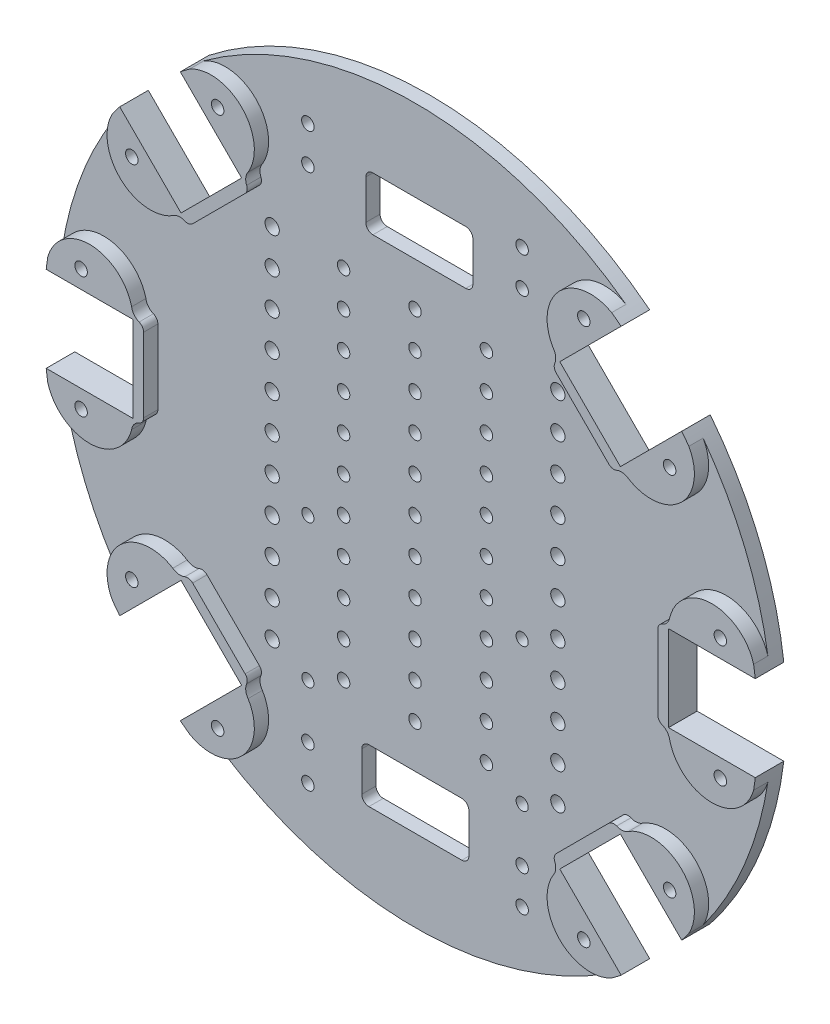
SolidWorks part; units mm, degrees
material "ABS PC"
ref_plane "Front Plane" through (0, 0, 0) normal (0, 0, 1) x (1, 0, 0)
ref_plane "Top Plane" through (0, 0, 0) normal (0, 1, 0) x (1, 0, 0)
ref_plane "Right Plane" through (0, 0, 0) normal (1, 0, 0) x (0, 0, -1)
sketch "Sketch1" plane through (0, 0, 0) normal (0, 0, 1) x (1, 0, 0)
  line L0 (0, 0) -> (0, 100) construction
  line L5 (44.5477, 61.5183) -> (61.7144, 78.685)
  line L6 (44.5477, 61.5183) -> (61.5183, 44.5477)
  line L7 (-12, 75) -> (12, 75) construction
  line L8 (-12, 75) -> (-12, 99.2774) construction
  line L9 (12, 75) -> (12, 99.2774) construction
  line L10 (-17, 89.5) -> (17, 89.5) construction
  line L11 (61.5183, 44.5477) -> (78.685, 61.7144)
  line L12 (75, 12) -> (99.2774, 12)
  line L13 (75, 12) -> (75, -12)
  line L14 (75, -12) -> (99.2774, -12)
  line L15 (61.5183, -44.5477) -> (78.685, -61.7144)
  line L16 (61.5183, -44.5477) -> (44.5477, -61.5183)
  line L17 (44.5477, -61.5183) -> (61.7144, -78.685)
  line L18 (12, -75) -> (12, -99.2774) construction
  line L19 (12, -75) -> (-12, -75) construction
  line L20 (-12, -75) -> (-12, -99.2774) construction
  line L21 (-44.5477, -61.5183) -> (-61.7144, -78.685)
  line L22 (-44.5477, -61.5183) -> (-61.5183, -44.5477)
  line L23 (-61.5183, -44.5477) -> (-78.685, -61.7144)
  line L24 (-75, -12) -> (-99.2774, -12)
  line L25 (-75, -12) -> (-75, 12)
  line L26 (-75, 12) -> (-99.2774, 12)
  line L27 (-61.5183, 44.5477) -> (-78.685, 61.7144)
  line L28 (-61.5183, 44.5477) -> (-44.5477, 61.5183)
  line L29 (-44.5477, 61.5183) -> (-61.7144, 78.685)
  circle A1 centre (0, 0) radius 100
  circle A2 centre (-17, 89.5) radius 1.75 construction
  circle A3 centre (17, 89.5) radius 1.75 construction
  circle A4 centre (51.2652, 75.3069) radius 1.75
  circle A5 centre (75.3069, 51.2652) radius 1.75
  circle A6 centre (89.5, 17) radius 1.75
  circle A7 centre (89.5, -17) radius 1.75
  circle A8 centre (75.3069, -51.2652) radius 1.75
  circle A9 centre (51.2652, -75.3069) radius 1.75
  circle A10 centre (17, -89.5) radius 1.75 construction
  circle A11 centre (-17, -89.5) radius 1.75 construction
  circle A12 centre (-51.2652, -75.3069) radius 1.75
  circle A13 centre (-75.3069, -51.2652) radius 1.75
  circle A14 centre (-89.5, -17) radius 1.75
  circle A15 centre (-89.5, 17) radius 1.75
  circle A16 centre (-75.3069, 51.2652) radius 1.75
  circle A17 centre (-51.2652, 75.3069) radius 1.75
  point P2 (0, 89.5)
  point P4 (0, 75)
  point P12 (0, 75)
  point P19 (0, 89.5)
  dimension "150" = 200
  dimension "D7" = 3.5
  dimension "D2" = 25
  dimension "D3" = 8
  dimension "D4" = 24
  dimension "D5" = 14.5
  dimension "D6" = 34
extrude "Boss-Extrude1" add sketch "Sketch1" along normal blind 4 contours L12 A1 L11 L6 L5 L29 L28 L27 L26 L25 L24 L23 L22 L21 L17 L16 L15 L14 L13 A15 A14 A9 A8 A5 A4 A6 A7 A12 A13 A16 A17
sketch "Sketch2" plane through (0, 0, 4) normal (0, 0, 1) x (1, 0, 0)
  line L0 (0, 35) -> (0, -35) construction
  line L1 (-35, 35) -> (35, 35) construction
  line L2 (-35, 35) -> (-35, -35) construction
  line L3 (-35, -35) -> (35, -35) construction
  line L4 (35, 35) -> (35, -35) construction
  line L5 (-35, 35) -> (35, -35) construction
  line L6 (-35, -35) -> (35, 35) construction
  line L7 (0, 35) -> (0, 80)
  line L8 (-30, -15) -> (30, -15) construction
  line L9 (-30, -15) -> (-30, -55) construction
  line L10 (-30, -55) -> (30, -55) construction
  line L11 (30, -15) -> (30, -55) construction
  line L12 (-30, -15) -> (30, -55) construction
  line L13 (-30, -55) -> (30, -15) construction
  line L14 (-30, 80) -> (30, 80)
  line L15 (0, -55) -> (0, -80)
  line L16 (30, -80) -> (-30, -80)
  line L17 (0, 0) -> (-40, 0) construction
  line L18 (0, 0) -> (40, 0) construction
  line L19 (0, 10) -> (-40, 10)
  line L20 (0, 10) -> (40, 10)
  line L21 (0, 20) -> (-40, 20)
  line L22 (0, 20) -> (40, 20)
  line L23 (0, 30) -> (-40, 30)
  line L24 (0, 30) -> (40, 30)
  line L25 (0, 40) -> (-40, 40)
  line L26 (0, 40) -> (40, 40)
  line L27 (0, 50) -> (-40, 50)
  line L28 (0, 50) -> (40, 50)
  line L29 (0, -10) -> (40, -10)
  line L30 (0, -10) -> (-40, -10)
  line L31 (0, -20) -> (40, -20)
  line L32 (0, -20) -> (-40, -20)
  line L33 (0, -30) -> (40, -30)
  line L34 (0, -30) -> (-40, -30)
  line L35 (0, -40) -> (40, -40)
  line L36 (0, -40) -> (-40, -40)
  line L37 (0, -50) -> (40, -50)
  line L38 (0, -50) -> (-40, -50)
  line L39 (30, -70) -> (-30, -70)
  line L40 (-30, 70) -> (30, 70)
  circle A0 centre (0, 0) radius 100
  circle A1 centre (-30, -55) radius 1.7
  circle A2 centre (-30, -15) radius 1.7
  circle A3 centre (30, -55) radius 1.7
  circle A4 centre (30, -15) radius 1.7
  circle A5 centre (-30, 80) radius 1.75
  circle A6 centre (30, 80) radius 1.75
  circle A7 centre (-30, -80) radius 1.75
  circle A8 centre (30, -80) radius 1.75
  circle A9 centre (-40, 0) radius 2
  circle A10 centre (-20, 0) radius 1.75
  circle A11 centre (0, 0) radius 1.75
  circle A12 centre (40, 0) radius 2
  circle A13 centre (20, 0) radius 1.75
  circle A14 centre (20, 10) radius 1.75
  circle A15 centre (40, 10) radius 2
  circle A16 centre (-20, 10) radius 1.75
  circle A17 centre (-40, 10) radius 2
  circle A18 centre (0, 10) radius 1.75
  circle A19 centre (20, 20) radius 1.75
  circle A20 centre (40, 20) radius 2
  circle A21 centre (-20, 20) radius 1.75
  circle A22 centre (-40, 20) radius 2
  circle A23 centre (0, 20) radius 1.75
  circle A24 centre (20, 30) radius 1.75
  circle A25 centre (40, 30) radius 2
  circle A26 centre (-20, 30) radius 1.75
  circle A27 centre (-40, 30) radius 2
  circle A28 centre (0, 30) radius 1.75
  circle A29 centre (20, 40) radius 1.75
  circle A30 centre (40, 40) radius 2
  circle A31 centre (-20, 40) radius 1.75
  circle A32 centre (-40, 40) radius 2
  circle A33 centre (0, 40) radius 1.75
  circle A34 centre (20, 50) radius 1.75
  circle A35 centre (40, 50) radius 2
  circle A36 centre (-20, 50) radius 1.75
  circle A37 centre (-40, 50) radius 2
  circle A38 centre (0, 50) radius 1.75
  circle A39 centre (40, -10) radius 2
  circle A40 centre (0, -10) radius 1.75
  circle A41 centre (20, -10) radius 1.75
  circle A42 centre (-20, -10) radius 1.75
  circle A43 centre (-40, -10) radius 2
  circle A44 centre (40, -20) radius 2
  circle A45 centre (0, -20) radius 1.75
  circle A46 centre (20, -20) radius 1.75
  circle A47 centre (-20, -20) radius 1.75
  circle A48 centre (-40, -20) radius 2
  circle A49 centre (40, -30) radius 2
  circle A50 centre (0, -30) radius 1.75
  circle A51 centre (20, -30) radius 1.75
  circle A52 centre (-20, -30) radius 1.75
  circle A53 centre (-40, -30) radius 2
  circle A54 centre (40, -40) radius 2
  circle A55 centre (0, -40) radius 1.75
  circle A56 centre (20, -40) radius 1.75
  circle A57 centre (-20, -40) radius 1.75
  circle A58 centre (-40, -40) radius 2
  circle A59 centre (40, -50) radius 2
  circle A60 centre (0, -50) radius 1.75
  circle A61 centre (20, -50) radius 1.75
  circle A62 centre (-20, -50) radius 1.75
  circle A63 centre (-40, -50) radius 2
  circle A64 centre (30, -70) radius 1.75
  circle A65 centre (-30, -70) radius 1.75
  circle A66 centre (-30, 70) radius 1.75
  circle A67 centre (30, 70) radius 1.75
  point P10 (0, 0)
  point P23 (0, 80)
  point P30 (0, -80)
  dimension "D1" = 200
  dimension "D6" = 3.4
  dimension "D9" = 3.5
  dimension "D10" = 3.5
  dimension "D13" = 3.5
  dimension "D14" = 3.5
  dimension "D16" = 4
  dimension "D17" = 3.5
  dimension "D18" = 3.5
  dimension "D2" = 70
  dimension "D3" = 70
  dimension "D4" = 40
  dimension "D5" = 60
  dimension "D7" = 45
  dimension "D8" = 60
  dimension "D11" = 25
  dimension "D12" = 60
  dimension "D15" = 40
  dimension "D19" = 6
  dimension "D20" = 6
  dimension "D21" = 2
  dimension "D22" = 2
extrude "Cut-Extrude1" cut sketch "Sketch2" against normal blind 10
sketch "Sketch3" plane through (0, 0, 4) normal (0, 0, 1) x (1, 0, 0)
  line L0 (-78.685, 61.7144) -> (-61.5183, 44.5477)
  line L1 (-61.5183, 44.5477) -> (-44.5477, 61.5183)
  line L2 (-44.5477, 61.5183) -> (-61.7144, 78.685)
  line L3 (-58.255, 43.5684) -> (-43.5684, 58.255)
  line L4 (-53.033, 53.033) -> (-50.9117, 50.9117)
  line L5 (-10.385, 72) -> (10.385, 72)
  line L6 (-12, 75) -> (12, 75)
  line L7 (-12, 99.2774) -> (-12, 75)
  line L8 (12, 75) -> (12, 99.2774)
  line L9 (43.5684, 58.255) -> (58.255, 43.5684)
  line L10 (44.5477, 61.5183) -> (61.5183, 44.5477)
  line L11 (61.7144, 78.685) -> (44.5477, 61.5183)
  line L12 (61.5183, 44.5477) -> (78.685, 61.7144)
  line L13 (72, 10.385) -> (72, -10.385)
  line L14 (75, 12) -> (75, -12)
  line L15 (99.2774, 12) -> (75, 12)
  line L16 (75, -12) -> (99.2774, -12)
  line L17 (58.255, -43.5684) -> (43.5684, -58.255)
  line L18 (61.5183, -44.5477) -> (44.5477, -61.5183)
  line L19 (78.685, -61.7144) -> (61.5183, -44.5477)
  line L20 (44.5477, -61.5183) -> (61.7144, -78.685)
  line L21 (10.385, -72) -> (-10.385, -72)
  line L22 (12, -75) -> (-12, -75)
  line L23 (12, -99.2774) -> (12, -75)
  line L24 (-12, -75) -> (-12, -99.2774)
  line L25 (-43.5684, -58.255) -> (-58.255, -43.5684)
  line L26 (-44.5477, -61.5183) -> (-61.5183, -44.5477)
  line L27 (-61.7144, -78.685) -> (-44.5477, -61.5183)
  line L28 (-61.5183, -44.5477) -> (-78.685, -61.7144)
  line L29 (-72, -10.385) -> (-72, 10.385)
  line L30 (-75, -12) -> (-75, 12)
  line L31 (-99.2774, -12) -> (-75, -12)
  line L32 (-75, 12) -> (-99.2774, 12)
  arc A1 (-12.2421, 73.2574) -> (-10.385, 72) centre (-10.385, 74) ccw
  circle A2 centre (0, 0) radius 100
  arc A3 (-61.5183, 44.5477) -> (-78.685, 61.7144) centre (-70.1016, 53.1311) cw
  arc A4 (-61.7144, 78.685) -> (-44.5477, 61.5183) centre (-53.1311, 70.1016) cw
  circle A5 centre (-51.2652, 75.3069) radius 1.75
  circle A6 centre (-75.3069, 51.2652) radius 1.75
  arc A7 (-43.1444, 60.4573) -> (-42.7452, 63.8182) centre (-40.0316, 61.7918) cw
  arc A8 (-60.4573, 43.1444) -> (-63.8182, 42.7452) centre (-61.7918, 40.0316) ccw
  arc A9 (-60.4573, 43.1444) -> (-58.255, 43.5684) centre (-59.6692, 44.9826) ccw
  arc A10 (-43.1444, 60.4573) -> (-43.5684, 58.255) centre (-44.9826, 59.6692) cw
  arc A11 (-12.2421, 73.2574) -> (-14.9009, 75.3517) centre (-15.3867, 72) ccw
  arc A12 (-12, 75) -> (-12, 99.2774) centre (-12, 87.1387) cw
  circle A13 centre (-17, 89.5) radius 1.75
  circle A14 centre (17, 89.5) radius 1.75
  arc A15 (12, 99.2774) -> (12, 75) centre (12, 87.1387) cw
  arc A16 (12.2421, 73.2574) -> (14.9009, 75.3517) centre (15.3867, 72) cw
  arc A17 (12.2421, 73.2574) -> (10.385, 72) centre (10.385, 74) cw
  arc A18 (43.1444, 60.4573) -> (43.5684, 58.255) centre (44.9826, 59.6692) ccw
  arc A19 (43.1444, 60.4573) -> (42.7452, 63.8182) centre (40.0316, 61.7918) ccw
  arc A20 (44.5477, 61.5183) -> (61.7144, 78.685) centre (53.1311, 70.1016) cw
  circle A21 centre (51.2652, 75.3069) radius 1.75
  circle A22 centre (75.3069, 51.2652) radius 1.75
  arc A23 (78.685, 61.7144) -> (61.5183, 44.5477) centre (70.1016, 53.1311) cw
  arc A24 (60.4573, 43.1444) -> (63.8182, 42.7452) centre (61.7918, 40.0316) cw
  arc A25 (60.4573, 43.1444) -> (58.255, 43.5684) centre (59.6692, 44.9826) cw
  arc A26 (73.2574, 12.2421) -> (72, 10.385) centre (74, 10.385) ccw
  arc A27 (73.2574, 12.2421) -> (75.3517, 14.9009) centre (72, 15.3867) ccw
  arc A28 (75, 12) -> (99.2774, 12) centre (87.1387, 12) cw
  circle A29 centre (89.5, 17) radius 1.75
  circle A30 centre (89.5, -17) radius 1.75
  arc A31 (99.2774, -12) -> (75, -12) centre (87.1387, -12) cw
  arc A32 (73.2574, -12.2421) -> (75.3517, -14.9009) centre (72, -15.3867) cw
  arc A33 (73.2574, -12.2421) -> (72, -10.385) centre (74, -10.385) cw
  arc A34 (60.4573, -43.1444) -> (58.255, -43.5684) centre (59.6692, -44.9826) ccw
  arc A35 (60.4573, -43.1444) -> (63.8182, -42.7452) centre (61.7918, -40.0316) ccw
  arc A36 (61.5183, -44.5477) -> (78.685, -61.7144) centre (70.1016, -53.1311) cw
  circle A37 centre (75.3069, -51.2652) radius 1.75
  circle A38 centre (51.2652, -75.3069) radius 1.75
  arc A39 (61.7144, -78.685) -> (44.5477, -61.5183) centre (53.1311, -70.1016) cw
  arc A40 (43.1444, -60.4573) -> (42.7452, -63.8182) centre (40.0316, -61.7918) cw
  arc A41 (43.1444, -60.4573) -> (43.5684, -58.255) centre (44.9826, -59.6692) cw
  arc A42 (12.2421, -73.2574) -> (10.385, -72) centre (10.385, -74) ccw
  arc A43 (12.2421, -73.2574) -> (14.9009, -75.3517) centre (15.3867, -72) ccw
  arc A44 (12, -75) -> (12, -99.2774) centre (12, -87.1387) cw
  circle A45 centre (17, -89.5) radius 1.75
  circle A46 centre (-17, -89.5) radius 1.75
  arc A47 (-12, -99.2774) -> (-12, -75) centre (-12, -87.1387) cw
  arc A48 (-12.2421, -73.2574) -> (-14.9009, -75.3517) centre (-15.3867, -72) cw
  arc A49 (-12.2421, -73.2574) -> (-10.385, -72) centre (-10.385, -74) cw
  arc A50 (-43.1444, -60.4573) -> (-43.5684, -58.255) centre (-44.9826, -59.6692) ccw
  arc A51 (-43.1444, -60.4573) -> (-42.7452, -63.8182) centre (-40.0316, -61.7918) ccw
  arc A52 (-44.5477, -61.5183) -> (-61.7144, -78.685) centre (-53.1311, -70.1016) cw
  circle A53 centre (-51.2652, -75.3069) radius 1.75
  circle A54 centre (-75.3069, -51.2652) radius 1.75
  arc A55 (-78.685, -61.7144) -> (-61.5183, -44.5477) centre (-70.1016, -53.1311) cw
  arc A56 (-60.4573, -43.1444) -> (-63.8182, -42.7452) centre (-61.7918, -40.0316) cw
  arc A57 (-60.4573, -43.1444) -> (-58.255, -43.5684) centre (-59.6692, -44.9826) cw
  arc A58 (-73.2574, -12.2421) -> (-72, -10.385) centre (-74, -10.385) ccw
  arc A59 (-73.2574, -12.2421) -> (-75.3517, -14.9009) centre (-72, -15.3867) ccw
  arc A60 (-75, -12) -> (-99.2774, -12) centre (-87.1387, -12) cw
  circle A61 centre (-89.5, -17) radius 1.75
  circle A62 centre (-89.5, 17) radius 1.75
  arc A63 (-99.2774, 12) -> (-75, 12) centre (-87.1387, 12) cw
  arc A64 (-73.2574, 12.2421) -> (-75.3517, 14.9009) centre (-72, 15.3867) cw
  arc A65 (-73.2574, 12.2421) -> (-72, 10.385) centre (-74, 10.385) cw
  point P29 (-59.397, 42.4264)
  point P32 (-42.4264, 59.397)
  dimension "D2" = 2
  dimension "D1" = 2
  dimension "D3" = 8
extrude "Boss-Extrude2" add sketch "Sketch3" along normal blind 4 contours A39 A40 A2 L20 A38 | A41 A40 A39 L18 A36 A35 A34 L17 | A36 L19 A2 A35 A37 | A31 A32 A2 L16 A30 | A33 A32 A31 L14 A28 A27 A26 L13 | A28 L15 A2 A27 A29 | A23 A24 A2 L12 A22 | A25 A24 A23 L10 A20 A19 A18 L9 | A20 L11 A2 A19 A21 | A4 A7 A2 L2 A5 | A10 A7 A4 L1 L4 L3 | A8 A9 L3 L4 L1 A3 | A8 A3 L0 A2 A6 | A63 A64 A2 L32 A62 | A65 A64 A63 L30 A60 A59 A58 L29 | A60 L31 A2 A59 A61 | A55 A56 A2 L28 A54 | A57 A56 A55 L26 A52 A51 A50 L25 | A52 L27 A2 A51 A53
sketch "Sketch4" plane through (0, 0, 4) normal (0, 0, 1) x (1, 0, 0)
  line L0 (14.2118, 62.1273) -> (-11.7882, 62.1273)
  line L1 (13.1, -77.0997) -> (-12.9, -77.0997)
  line L2 (15.1, -75.0997) -> (15.1, -64.0997)
  line L3 (13.1, -62.0997) -> (-12.9, -62.0997)
  line L4 (-14.9, -75.0997) -> (-14.9, -64.0997)
  line L5 (15.1, -77.0997) -> (-14.9, -62.0997) construction
  line L6 (15.1, -62.0997) -> (-14.9, -77.0997) construction
  line L7 (16.2118, 64.1273) -> (16.2118, 75.1273)
  line L8 (14.2118, 77.1273) -> (-11.7882, 77.1273)
  line L9 (-13.7882, 64.1273) -> (-13.7882, 75.1273)
  arc A0 (-14.9, -75.0997) -> (-12.9, -77.0997) centre (-12.9, -75.0997) ccw
  arc A1 (-14.9, -64.0997) -> (-12.9, -62.0997) centre (-12.9, -64.0997) cw
  arc A2 (13.1, -62.0997) -> (15.1, -64.0997) centre (13.1, -64.0997) cw
  arc A3 (13.1, -77.0997) -> (15.1, -75.0997) centre (13.1, -75.0997) ccw
  arc A4 (-13.7882, 64.1273) -> (-11.7882, 62.1273) centre (-11.7882, 64.1273) ccw
  arc A5 (-13.7882, 75.1273) -> (-11.7882, 77.1273) centre (-11.7882, 75.1273) cw
  arc A6 (14.2118, 77.1273) -> (16.2118, 75.1273) centre (14.2118, 75.1273) cw
  arc A7 (14.2118, 62.1273) -> (16.2118, 64.1273) centre (14.2118, 64.1273) ccw
  point P0 (0.1, -69.5997)
  dimension "D3" = 2
  dimension "D1" = 15
  dimension "D2" = 30
extrude "Cut-Extrude2" cut sketch "Sketch4" against normal blind 10 contours L1 A3 L2 A2 L3 A1 L4 A0 | L0 A4 L9 A5 L8 A6 L7 A7
